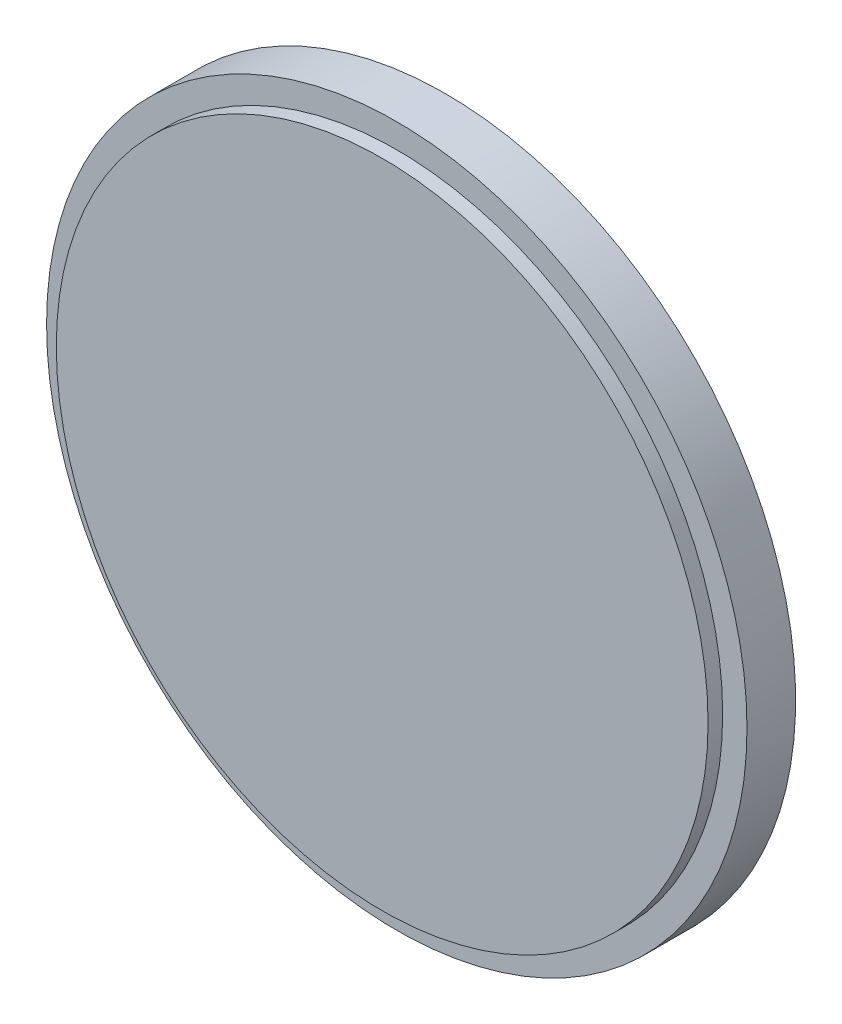
SolidWorks part; units mm, degrees
material "Liga 1060"
ref_plane "Plano frontal" through (0, 0, 0) normal (0, 0, 1) x (1, 0, 0)
ref_plane "Plano superior" through (0, 0, 0) normal (0, 1, 0) x (1, 0, 0)
ref_plane "Plano direito" through (0, 0, 0) normal (1, 0, 0) x (0, 0, -1)
sketch "Esboço1" plane through (0, 0, 0) normal (0, 0, 1) x (1, 0, 0)
  circle A0 centre (0, 0) radius 32.5
  circle A1 centre (0, 0) radius 35
extrude "Ressalto-extrusão1" add sketch "Esboço1" along normal blind 8
sketch "Esboço2" plane through (0, 0, 8) normal (0, 0, 1) x (1, 0, 0)
  circle A0 centre (0, 0) radius 32.5
extrude "Ressalto-extrusão2" add sketch "Esboço2" against normal blind 3
sketch "Esboço3" plane through (0, 0, 8) normal (0, 0, 1) x (1, 0, 0)
  circle A0 centre (0, 0) radius 2.5
extrude "Corte-extrusão1" cut sketch "Esboço3" against normal blind 3
sketch "Esboço4" plane through (0, 0, 5) normal (0, 0, -1) x (-1, 0, 0)
  circle A0 centre (0, 0) radius 37
  circle A1 centre (0, 0) radius 35
extrude "Ressalto-extrusão3" add sketch "Esboço4" against normal through all and the other way through all
sketch "Esboço5" plane through (0, 0, 0) normal (0, 1, 0) x (1, 0, 0)
  line L0 (-37, -1) -> (-37, -7)
  line L1 (-37, -4) -> (-13.2615, -4)
  line L2 (-35.2, -4) -> (-35.2, -1)
  line L3 (-35.2, -1) -> (-37, -1)
  line L4 (-35.2, -4) -> (-35.2, -7)
  line L5 (-35.2, -7) -> (-37, -7)
revolve "Corte-Revolução1" cut sketch "Esboço5" angle 360 about axis through (0, 0, 8) along (0, 0, -1)
sketch "Esboço6" plane through (0, 0, 5) normal (0, 0, -1) x (-1, 0, 0)
  circle A0 centre (0, 0) radius 12.55
  dimension "D1" = 25.1
extrude "Ressalto-extrusão4" add sketch "Esboço6" along normal blind 5
sketch "Esboço7" plane through (0, 0, 0) normal (0, 0, -1) x (-1, 0, 0)
  circle A0 centre (0, 0) radius 7.55
  dimension "D1" = 15.1
extrude "Corte-extrusão2" cut sketch "Esboço7" against normal through all both and the other way through all
sketch "Esboço8" plane through (0, 0, 8) normal (0, 0, 1) x (1, 0, 0)
  circle A0 centre (0, 0) radius 37
  circle A1 centre (0, 0) radius 32.5
  dimension "D1" = 74
extrude "Ressalto-extrusão5" add sketch "Esboço8" against normal up to surface (8 mm away) up to face at (32.5, 0, 0)
sketch "Esboço9" plane through (0, 0, 8) normal (0, 0, 1) x (1, 0, 0)
  circle A0 centre (0, 0) radius 37
  circle A1 centre (0, 0) radius 33.5
extrude "Corte-extrusão8" cut sketch "Esboço9" against normal blind 1.5
sketch "Esboço12" plane through (0, 0, 0) normal (0, 0, -1) x (-1, 0, 0)
  circle A0 centre (0, 0) radius 37
  circle A1 centre (0, 0) radius 33.5
  dimension "D1" = 74
extrude "Corte-extrusão9" cut sketch "Esboço12" against normal blind 1.5
sketch "Esboço13" plane through (0, 0, 1.5) normal (0, 0, -1) x (-1, 0, 0)
  circle A1 centre (0, 0) radius 36
  circle A2 centre (0, 0) radius 37
extrude "Corte-extrusão10" cut sketch "Esboço13" against normal blind 10
sketch "Esboço14" plane through (0, 0, 6.5) normal (0, 0, 1) x (1, 0, 0)
  circle A0 centre (0, 0) radius 37
  circle A1 centre (0, 0) radius 36
  circle A3 centre (0, 0) radius 36
  circle A6 centre (0, 0) radius 36
  circle M3 centre (0, 0) radius 36
  dimension "D1" = 0
extrude "Ressalto-extrusão6" add sketch "Esboço14" against normal up to surface (5 mm away) contours A0 M3 up to face at (-33.5, 0, 1.5)
sketch "Esboço15" plane through (0, 0, 0) normal (0, 0, -1) x (-1, 0, 0)
  circle A0 centre (0, 0) radius 12.55
extrude "Corte-extrusão11" cut sketch "Esboço15" against normal through all
sketch "Esboço16" plane through (0, 0, 5) normal (0, 0, -1) x (-1, 0, 0)
  circle A0 centre (0, 0) radius 12.55 construction
  circle A1 centre (0, 0) radius 12.55
extrude "Ressalto-extrusão7" add sketch "Esboço16" against normal through all
sketch "Esboço17" plane through (0, 0, 5) normal (0, 0, -1) x (-1, 0, 0)
  circle A0 centre (0, 0) radius 10
  dimension "D1" = 20
extrude "Ressalto-extrusão8" add sketch "Esboço17" along normal blind 16
sketch "Esboço18" plane through (0, 0, -11) normal (0, 0, -1) x (-1, 0, 0)
  circle A0 centre (0, 0) radius 3.3
  dimension "D1" = 6.6
extrude "Corte-extrusão12" cut sketch "Esboço18" against normal blind 16
sketch "Esboço23" plane through (0, 0, 1.5) normal (0, 0, -1) x (-1, 0, 0)
  circle A0 centre (0, 0) radius 36
  circle A1 centre (0, 0) radius 37 construction
  circle A2 centre (0, 0) radius 37
  dimension "D1" = 72
extrude "Corte-extrusão15" cut sketch "Esboço23" against normal through all
sketch "Esboço24" plane through (0, 0, -11) normal (0, 0, -1) x (-1, 0, 0)
  line L0 (0, 0) -> (0, 1.1) construction
  line L1 (-1.2298, 1.1) -> (1.2298, 1.1)
  arc A0 (-1.2298, 1.1) -> (1.2298, 1.1) centre (0, 0) ccw
  circle A1 centre (0, 0) radius 3.3 construction
  circle A2 centre (0, 0) radius 3.3
  point P7 (0, 1.1)
  dimension "D1" = 3.3
  dimension "D2" = 1.1
extrude "Ressalto-extrusão9" add sketch "Esboço24" against normal blind 11
sketch "Esboço21" plane through (0, 5.3, 0) normal (0, 1, 0) x (1, 0, 0)
  line L0 (0, 6.85) -> (0, 11) construction
  line L2 (-1.2298, 11) -> (1.2298, 11) construction
  line L3 (10, 11) -> (-10, 11) construction
  circle A0 centre (0, 6.85) radius 2.2
  dimension "D2" = 4.4
  dimension "D1" = 4.15
extrude "Corte-extrusão14" cut sketch "Esboço21" against normal through all both and the other way through all
